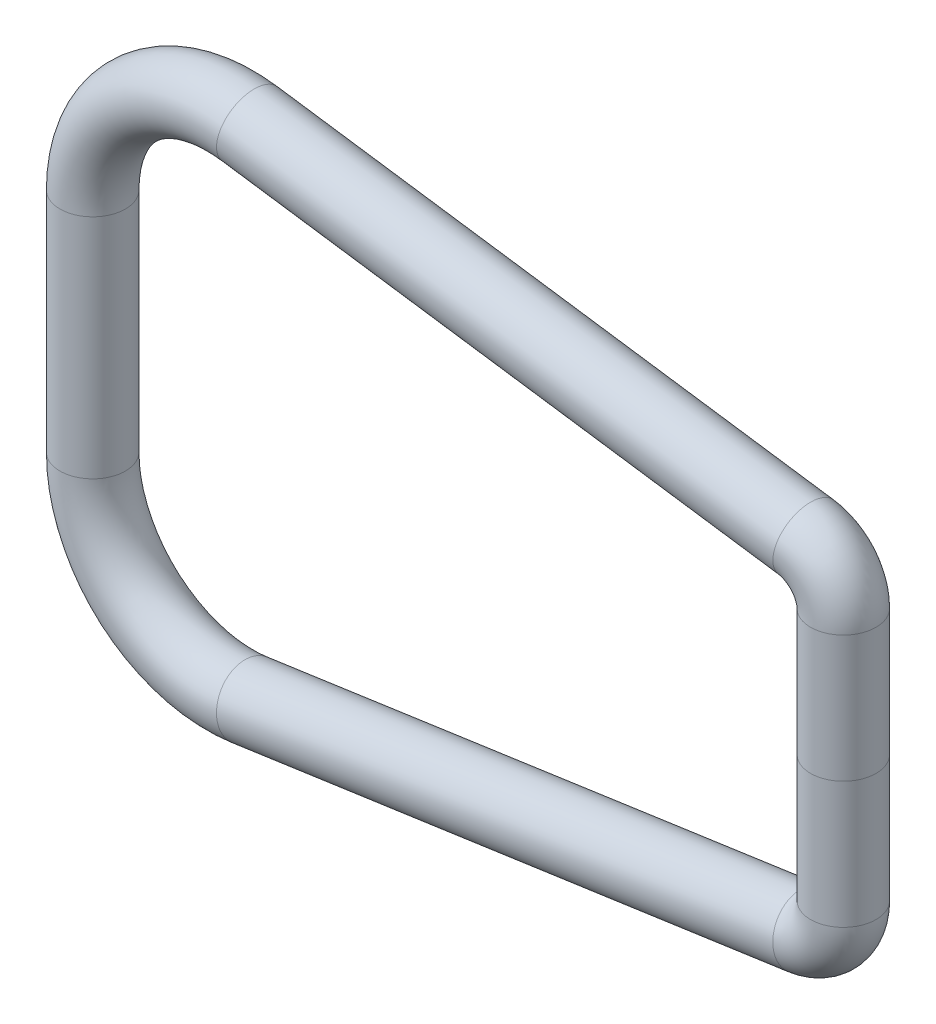
SolidWorks part; units mm, degrees
ref_plane "Front Plane" through (0, 0, 0) normal (0, 0, 1) x (1, 0, 0)
ref_plane "Top Plane" through (0, 0, 0) normal (0, 1, 0) x (1, 0, 0)
ref_plane "Right Plane" through (0, 0, 0) normal (1, 0, 0) x (0, 0, -1)
sketch "Sketch1" plane through (0, 0, 0) normal (0, 1, 0) x (0, 0, -1)
  circle A0 centre (0, 0) radius 0.9525
  dimension "D1" = 1.905
sketch "Sketch2" plane through (0, 0, 0) normal (0, 0, 1) x (1, 0, 0)
  line L2 (0, 3.683) -> (0, -3.683)
  line L4 (-21.844, -3.302) -> (-21.844, 3.302)
  line L5 (-17.2789, 7.2596) -> (-1.0899, 4.9402)
  line L6 (-17.2789, -7.2596) -> (-1.0899, -4.9402)
  arc A1 (-1.0899, -4.9402) -> (0, -3.683) centre (-1.27, -3.683) ccw
  arc A2 (0, 3.683) -> (-1.0899, 4.9402) centre (-1.27, 3.683) ccw
  arc A3 (-21.844, 3.302) -> (-17.2789, 7.2596) centre (-17.846, 3.302) cw
  arc A6 (-21.844, -3.302) -> (-17.2789, -7.2596) centre (-17.846, -3.302) ccw
  point P8 (-21.844, 0)
  point P12 (0, 0)
  point P14 (0, 0)
  point P16 (-13.5036, -13.3021)
  point P17 (0, 0)
  dimension "D1" = 6.604
  dimension "D2" = 7.366
  dimension "D4" = 2.54
  dimension "D7" = 9.8803
  dimension "D3" = 21.844
sweep "Sweep1" add profiles "Sketch1" path "Sketch2"
